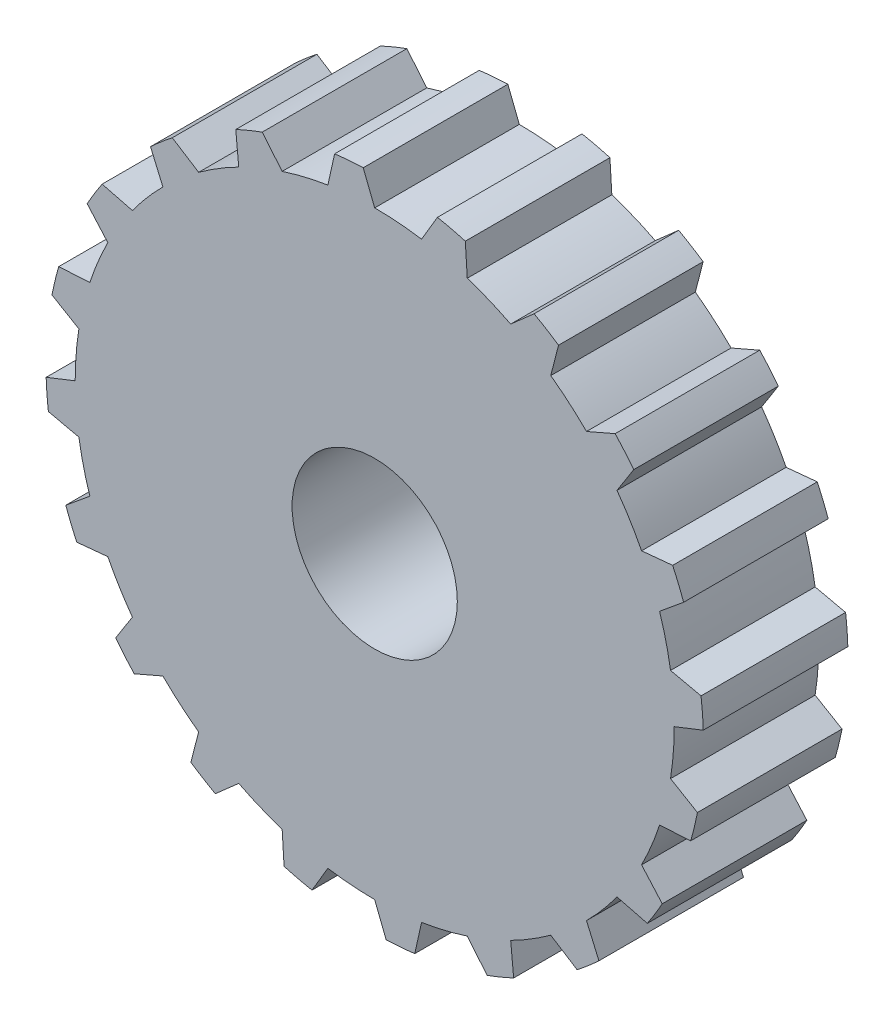
SolidWorks part; units mm, degrees
ref_plane "Front Plane" through (0, 0, 0) normal (0, 0, 1) x (1, 0, 0)
ref_plane "Top Plane" through (0, 0, 0) normal (0, 1, 0) x (1, 0, 0)
ref_plane "Right Plane" through (0, 0, 0) normal (1, 0, 0) x (0, 0, -1)
ref_plane "Plane1" through (0, 0, 7) normal (0, 0, 1) x (1, 0, 0)
sketch "Sketch1" plane through (0, 0, 7) normal (0, 0, 1) x (1, 0, 0)
  line L0 (16.2969, 1.9396) -> (14.8215, 2.2683)
  line L1 (14.2903, 4.4807) -> (15.4557, 5.4434)
  line L2 (14.9243, 6.7262) -> (13.4196, 6.5829)
  line L3 (12.2307, 8.5229) -> (13.0416, 9.7986)
  line L4 (12.1399, 10.8543) -> (10.753, 10.253)
  line L5 (9.0229, 11.7307) -> (9.3998, 13.1945)
  line L6 (8.216, 13.92) -> (7.0829, 12.9196)
  line L7 (4.9807, 13.7903) -> (4.8869, 15.299)
  line L8 (3.5368, 15.6231) -> (2.7683, 14.3215)
  line L9 (0.5, 14.5) -> (-0.0554, 15.9058)
  line L10 (-1.4396, 15.7969) -> (-1.7683, 14.3215)
  line L11 (-3.9807, 13.7903) -> (-4.9434, 14.9557)
  line L12 (-6.2262, 14.4243) -> (-6.0829, 12.9196)
  line L13 (-8.0229, 11.7307) -> (-9.2986, 12.5416)
  line L14 (-10.3543, 11.6399) -> (-9.753, 10.253)
  line L15 (-11.2307, 8.5229) -> (-12.6945, 8.8998)
  line L16 (-13.42, 7.716) -> (-12.4196, 6.5829)
  line L17 (-13.2903, 4.4807) -> (-14.799, 4.3869)
  line L18 (-15.1231, 3.0368) -> (-13.8215, 2.2683)
  line L19 (-14, 0) -> (-15.4058, -0.5554)
  line L20 (-15.2969, -1.9396) -> (-13.8215, -2.2683)
  line L21 (-13.2903, -4.4807) -> (-14.4557, -5.4434)
  line L22 (-13.9243, -6.7262) -> (-12.4196, -6.5829)
  line L23 (-11.2307, -8.5229) -> (-12.0416, -9.7986)
  line L24 (-11.1399, -10.8543) -> (-9.753, -10.253)
  line L25 (-8.0229, -11.7307) -> (-8.3998, -13.1945)
  line L26 (-7.216, -13.92) -> (-6.0829, -12.9196)
  line L27 (-3.9807, -13.7903) -> (-3.8869, -15.299)
  line L28 (-2.5368, -15.6231) -> (-1.7683, -14.3215)
  line L29 (0.5, -14.5) -> (1.0554, -15.9058)
  line L30 (2.4396, -15.7969) -> (2.7683, -14.3215)
  line L31 (4.9807, -13.7903) -> (5.9434, -14.9557)
  line L32 (7.2262, -14.4243) -> (7.0829, -12.9196)
  line L33 (9.0229, -11.7307) -> (10.2986, -12.5416)
  line L34 (11.3543, -11.6399) -> (10.753, -10.253)
  line L35 (12.2307, -8.5229) -> (13.6945, -8.8998)
  line L36 (14.42, -7.716) -> (13.4196, -6.5829)
  line L37 (14.2903, -4.4807) -> (15.799, -4.3869)
  line L38 (16.1231, -3.0368) -> (14.8215, -2.2683)
  line L39 (15, 0) -> (16.4058, 0.5554)
  arc A0 (14.8215, 2.2683) -> (14.2903, 4.4807) centre (0.5, 0) ccw
  arc A1 (15.4557, 5.4434) -> (14.9243, 6.7262) centre (0.5, 0) ccw
  arc A2 (13.4196, 6.5829) -> (12.2307, 8.5229) centre (0.5, 0) ccw
  arc A3 (13.0416, 9.7986) -> (12.1399, 10.8543) centre (0.5, 0) ccw
  arc A4 (10.753, 10.253) -> (9.0229, 11.7307) centre (0.5, 0) ccw
  arc A5 (9.3998, 13.1945) -> (8.216, 13.92) centre (0.5, 0) ccw
  arc A6 (7.0829, 12.9196) -> (4.9807, 13.7903) centre (0.5, 0) ccw
  arc A7 (4.8869, 15.299) -> (3.5368, 15.6231) centre (0.5, 0) ccw
  arc A8 (2.7683, 14.3215) -> (0.5, 14.5) centre (0.5, 0) ccw
  arc A9 (-0.0554, 15.9058) -> (-1.4396, 15.7969) centre (0.5, 0) ccw
  arc A10 (-1.7683, 14.3215) -> (-3.9807, 13.7903) centre (0.5, 0) ccw
  arc A11 (-4.9434, 14.9557) -> (-6.2262, 14.4243) centre (0.5, 0) ccw
  arc A12 (-6.0829, 12.9196) -> (-8.0229, 11.7307) centre (0.5, 0) ccw
  arc A13 (-9.2986, 12.5416) -> (-10.3543, 11.6399) centre (0.5, 0) ccw
  arc A14 (-9.753, 10.253) -> (-11.2307, 8.5229) centre (0.5, 0) ccw
  arc A15 (-12.6945, 8.8998) -> (-13.42, 7.716) centre (0.5, 0) ccw
  arc A16 (-12.4196, 6.5829) -> (-13.2903, 4.4807) centre (0.5, 0) ccw
  arc A17 (-14.799, 4.3869) -> (-15.1231, 3.0368) centre (0.5, 0) ccw
  arc A18 (-13.8215, 2.2683) -> (-14, 0) centre (0.5, 0) ccw
  arc A19 (-15.4058, -0.5554) -> (-15.2969, -1.9396) centre (0.5, 0) ccw
  arc A20 (-13.8215, -2.2683) -> (-13.2903, -4.4807) centre (0.5, 0) ccw
  arc A21 (-14.4557, -5.4434) -> (-13.9243, -6.7262) centre (0.5, 0) ccw
  arc A22 (-12.4196, -6.5829) -> (-11.2307, -8.5229) centre (0.5, 0) ccw
  arc A23 (-12.0416, -9.7986) -> (-11.1399, -10.8543) centre (0.5, 0) ccw
  arc A24 (-9.753, -10.253) -> (-8.0229, -11.7307) centre (0.5, 0) ccw
  arc A25 (-8.3998, -13.1945) -> (-7.216, -13.92) centre (0.5, 0) ccw
  arc A26 (-6.0829, -12.9196) -> (-3.9807, -13.7903) centre (0.5, 0) ccw
  arc A27 (-3.8869, -15.299) -> (-2.5368, -15.6231) centre (0.5, 0) ccw
  arc A28 (-1.7683, -14.3215) -> (0.5, -14.5) centre (0.5, 0) ccw
  arc A29 (1.0554, -15.9058) -> (2.4396, -15.7969) centre (0.5, 0) ccw
  arc A30 (2.7683, -14.3215) -> (4.9807, -13.7903) centre (0.5, 0) ccw
  arc A31 (5.9434, -14.9557) -> (7.2262, -14.4243) centre (0.5, 0) ccw
  arc A32 (7.0829, -12.9196) -> (9.0229, -11.7307) centre (0.5, 0) ccw
  arc A33 (10.2986, -12.5416) -> (11.3543, -11.6399) centre (0.5, 0) ccw
  arc A34 (10.753, -10.253) -> (12.2307, -8.5229) centre (0.5, 0) ccw
  arc A35 (13.6945, -8.8998) -> (14.42, -7.716) centre (0.5, 0) ccw
  arc A36 (13.4196, -6.5829) -> (14.2903, -4.4807) centre (0.5, 0) ccw
  arc A37 (15.799, -4.3869) -> (16.1231, -3.0368) centre (0.5, 0) ccw
  arc A38 (14.8215, -2.2683) -> (15, 0) centre (0.5, 0) ccw
  arc A39 (16.4058, 0.5554) -> (16.2969, 1.9396) centre (0.5, 0) ccw
  circle A40 centre (0.5, 0) radius 4
extrude "Boss-Extrude1" add sketch "Sketch1" against normal blind 7
